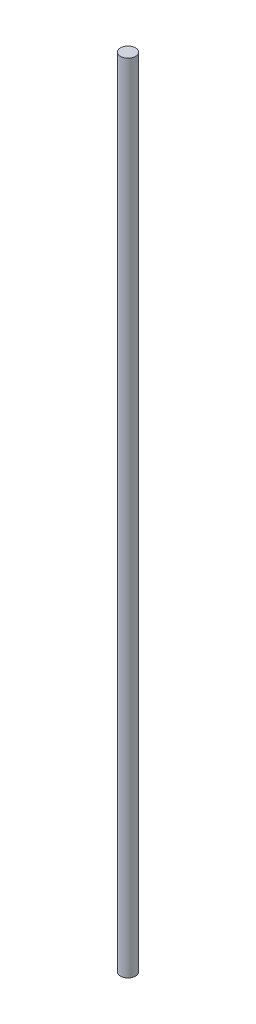
SolidWorks part; units mm, degrees
ref_plane "Front Plane" through (0, 0, 0) normal (0, 0, 1) x (1, 0, 0)
ref_plane "Top Plane" through (0, 0, 0) normal (0, 1, 0) x (1, 0, 0)
ref_plane "Right Plane" through (0, 0, 0) normal (1, 0, 0) x (0, 0, -1)
sketch "Sketch1" plane through (0, 0, 0) normal (0, 1, 0) x (1, 0, 0)
  circle A0 centre (0, 0) radius 1.5
  dimension "D1" = 3
extrude "Boss-Extrude1" add sketch "Sketch1" along normal blind 160
